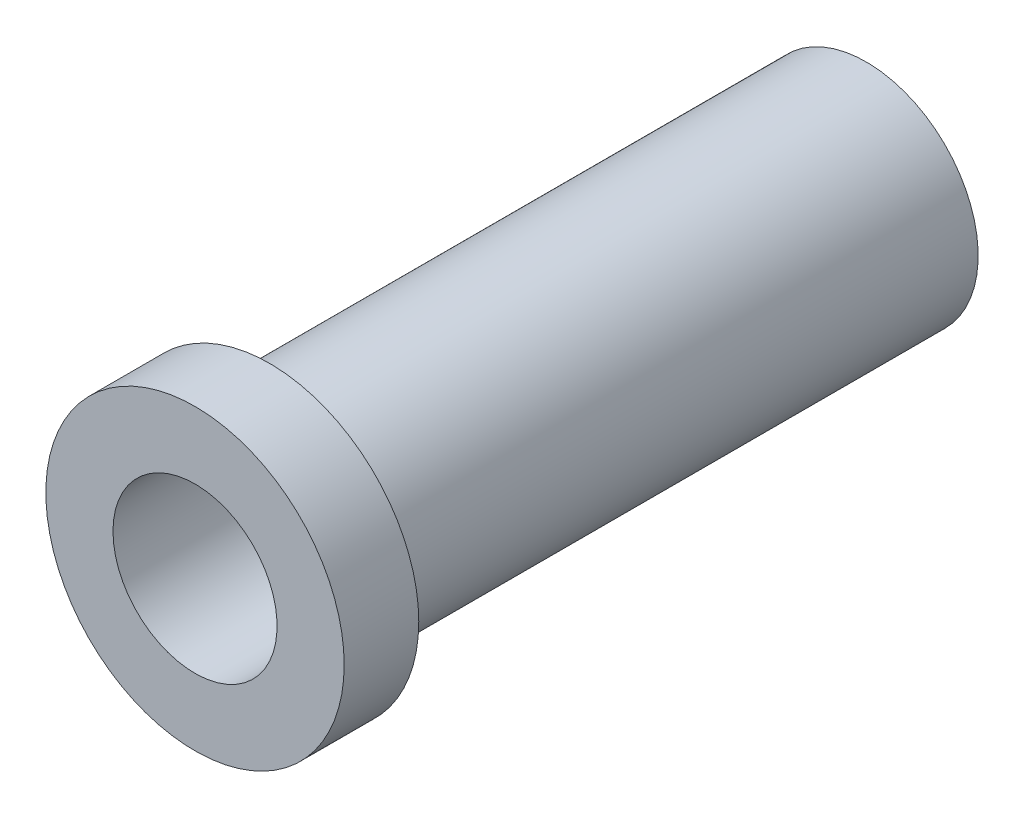
SolidWorks part; units mm, degrees
ref_plane "Front Plane" through (0, 0, 0) normal (0, 0, 1) x (1, 0, 0)
ref_plane "Top Plane" through (0, 0, 0) normal (0, 1, 0) x (1, 0, 0)
ref_plane "Right Plane" through (0, 0, 0) normal (1, 0, 0) x (0, 0, -1)
sketch "Sketch2" plane through (0, 0, 0) normal (0, 0, 1) x (1, 0, 0)
  circle A0 centre (0, 0) radius 10
  dimension "D1" = 20
extrude "Boss-Extrude1" add sketch "Sketch2" along normal blind 5
sketch "Sketch3" plane through (0, 0, 0) normal (0, 0, -1) x (-1, 0, 0)
  circle A0 centre (0, 0) radius 7.5
  dimension "D1" = 15
extrude "Boss-Extrude2" add sketch "Sketch3" along normal blind 40
sketch "Sketch4" plane through (0, 0, -40) normal (0, 0, -1) x (-1, 0, 0)
  circle A0 centre (0, 0) radius 5.5
  dimension "D1" = 11
extrude "Cut-Extrude1" cut sketch "Sketch4" against normal through all
